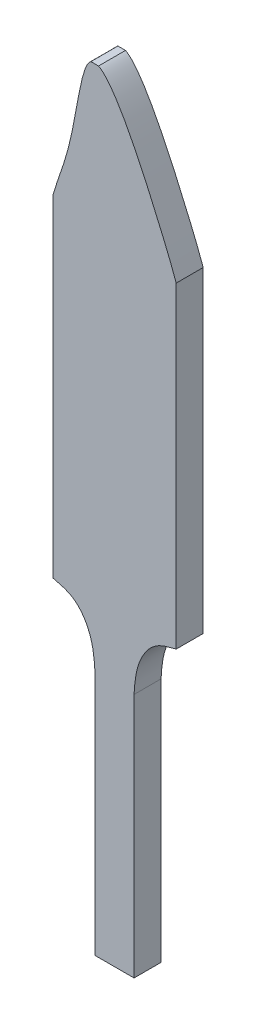
SolidWorks part; units mm, degrees
ref_plane "Front Plane" through (0, 0, 0) normal (0, 0, 1) x (1, 0, 0)
ref_plane "Top Plane" through (0, 0, 0) normal (0, 1, 0) x (1, 0, 0)
ref_plane "Right Plane" through (0, 0, 0) normal (1, 0, 0) x (0, 0, -1)
sketch "Sketch5" plane through (0, 0, 0) normal (0, 0, 1) x (1, 0, 0)
  line L0 (0, 0) -> (0, -10) construction
  line L1 (-6.2144, 150) -> (-9.1814, 150)
  line L2 (23.975, 92.039) -> (23.975, -31.1282)
  line L3 (7.5959, -150) -> (-7.5959, -150)
  line L4 (-23.975, 97.5505) -> (-23.975, -31.1282)
  line L5 (17.3514, 108.559) -> (-23.975, -150) construction
  line L6 (7.5959, -150) -> (-7.6179, 150.4334) construction
  line L7 (0, -10) -> (0, -20) construction
  line L8 (0, -20) -> (0, -150) construction
  line L9 (7.5959, -54.5936) -> (7.5959, -150)
  line L10 (-7.5959, -54.5936) -> (-7.5959, -150)
  spline S0 degree 3 poles (23.975, -31.1282) (21.2931, -31.7806) (13.9257, -33.5728) (8.2948, -44.0122) (7.7918, -51.6279) (7.5959, -54.5936) knots 0 0 0 0 0.258985 0.711437 1 1 1 1
  spline S1 degree 3 poles (-23.975, 97.5505) (-22.5251, 102.7973) (-14.8305, 121.3969) (-11.9489, 171.2076) (10.8617, 124.4724) (22.1155, 97.2664) (23.975, 92.039) knots 0.316421 0.316421 0.316421 0.316421 0.391637 0.56041 0.789537 0.848897 0.848897 0.848897 0.848897
  spline S2 degree 3 poles (-23.975, -31.1282) (-21.2931, -31.7806) (-13.9257, -33.5728) (-8.2948, -44.0122) (-7.7918, -51.6279) (-7.5959, -54.5936) knots 0 0 0 0 0.258985 0.711437 1 1 1 1
  point P0 (0, 0)
  point P6 (-23.975, 82.9218)
  point P7 (-5.9733, 117.9581)
  point P8 (-9.1814, 150)
  point P9 (17.3514, 108.559)
  point P10 (23.975, 63.8479)
  point P21 (23.975, -31.1282)
  point P23 (16.3746, -33.8322)
  point P24 (8.74, -45.2841)
  dimension "D1" = 10
  dimension "D2" = 10
  dimension "D3" = 130
  dimension "D4" = 150
extrude "Boss-Extrude1" add sketch "Sketch5" along normal blind 8.49 and the other way blind 2 contours L4 S2 L10 L3 L9 S0 L2 S1 L1
